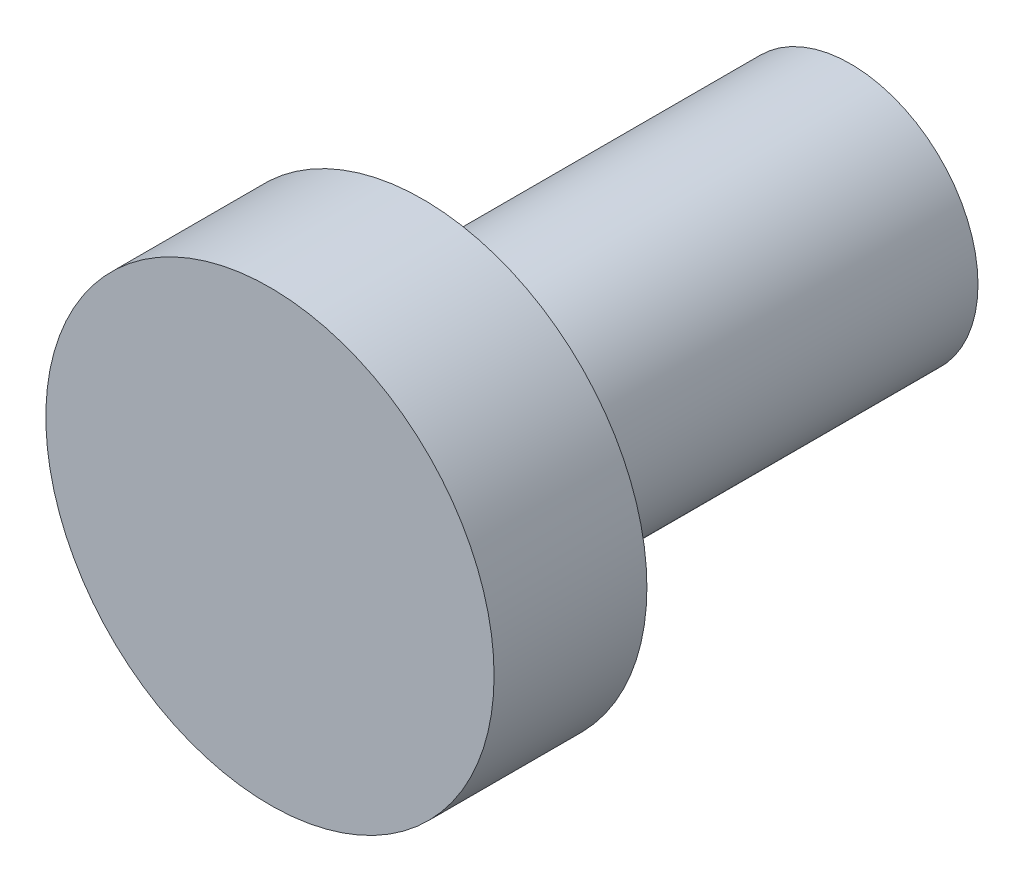
SolidWorks part; units mm, degrees
ref_plane "前视基准面" through (0, 0, 0) normal (0, 0, 1) x (1, 0, 0)
ref_plane "上视基准面" through (0, 0, 0) normal (0, 1, 0) x (1, 0, 0)
ref_plane "右视基准面" through (0, 0, 0) normal (1, 0, 0) x (0, 0, -1)
other "Configuration Table"
sketch "草图1" plane through (0, 0, 0) normal (0, 0, 1) x (1, 0, 0)
  circle A0 centre (0, 0) radius 1.25
extrude "M2p5转轴简化杆" add sketch "草图1" along normal blind 4.2
sketch "草图2" plane through (0, 0, 0) normal (0, 0, 1) x (1, 0, 0)
  circle A0 centre (0, 0) radius 2.2
extrude "转轴螺钉头包络" add sketch "草图2" along normal blind 1.5 from offset 4.2
